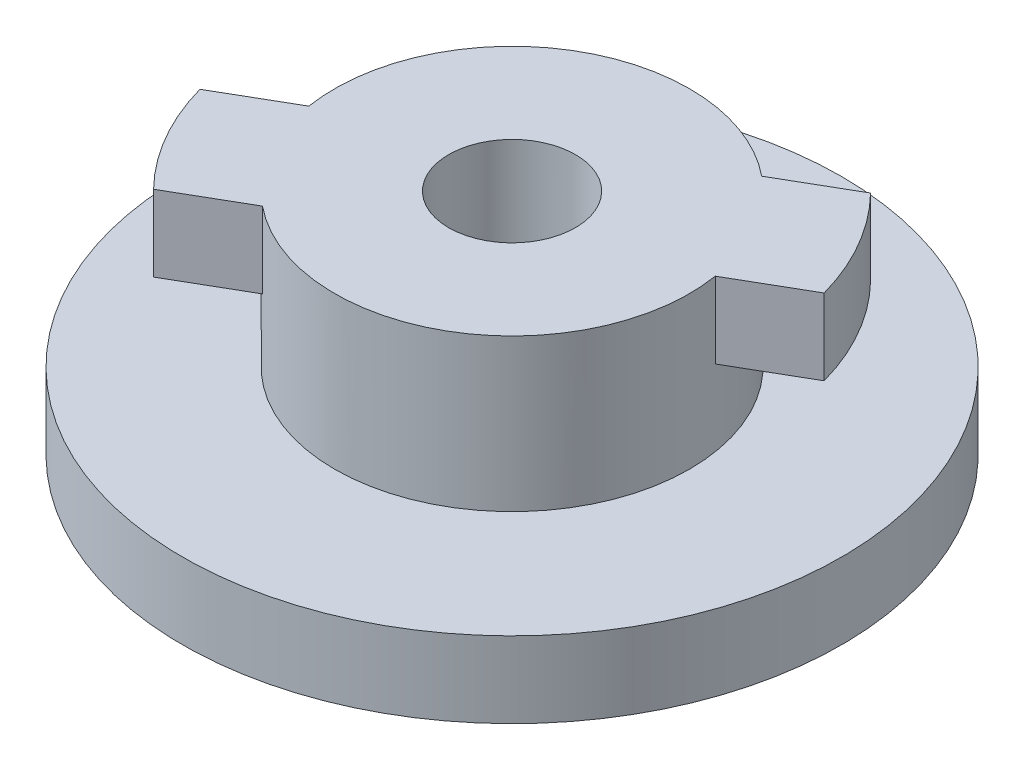
SolidWorks part; units mm, degrees
ref_plane "Front Plane" through (0, 0, 0) normal (0, 0, 1) x (1, 0, 0)
ref_plane "Top Plane" through (0, 0, 0) normal (0, 1, 0) x (1, 0, 0)
ref_plane "Right Plane" through (0, 0, 0) normal (1, 0, 0) x (0, 0, -1)
sketch "Sketch1" plane through (0, 0, 0) normal (0, 1, 0) x (-1, 0, 0)
  line L0 (0, -63.094) -> (22.5167, -50.094) construction
  line L1 (4.4124, -57.6598) -> (7.1353, -56.0877)
  line L2 (6.9124, -61.9899) -> (9.6353, -60.4178)
  line L9 (-4.4124, -68.5282) -> (-7.1353, -70.1003)
  line L10 (-6.9124, -64.1981) -> (-9.6353, -65.7702)
  arc A29 (-9.6353, -65.7702) -> (-7.1353, -70.1003) centre (0, -63.094) ccw
  arc A30 (-6.9124, -64.1981) -> (-4.4124, -68.5282) centre (0, -63.094) ccw construction
  arc A31 (7.1353, -56.0877) -> (-9.6353, -65.7702) centre (0, -63.094) ccw construction
  arc A32 (4.4124, -57.6598) -> (-6.9124, -64.1981) centre (0, -63.094) ccw
  arc A33 (6.9124, -61.9899) -> (4.4124, -57.6598) centre (0, -63.094) ccw construction
  arc A34 (-4.4124, -68.5282) -> (6.9124, -61.9899) centre (0, -63.094) ccw
  arc A35 (9.6353, -60.4178) -> (7.1353, -56.0877) centre (0, -63.094) ccw
  arc A36 (-7.1353, -70.1003) -> (9.6353, -60.4178) centre (0, -63.094) ccw construction
  dimension "D3" = 2
  dimension "D2" = 2.5
extrude "Boss-Extrude1" add sketch "Sketch1" along normal blind 3
sketch "Sketch2" plane through (0, 0, 0) normal (0, -1, 0) x (1, 0, 0)
  circle A0 centre (0, -63.094) radius 7
  arc A1 (-6.9124, -61.9899) -> (4.4124, -68.5282) centre (0, -63.094) ccw construction
extrude "Boss-Extrude2" add sketch "Sketch2" along normal blind 3
sketch "Sketch3" plane through (0, -3, 0) normal (0, -1, 0) x (1, 0, 0)
  circle A0 centre (0, -63.094) radius 7 construction
  circle A2 centre (0, -63.094) radius 7 construction
  circle A3 centre (0, -63.094) radius 13
  dimension "D1" = 26
extrude "Boss-Extrude3" add sketch "Sketch3" along normal blind 3
sketch "Sketch4" plane through (0, 3, 0) normal (0, 1, 0) x (1, 0, 0)
  circle A0 centre (0, 63.094) radius 7 construction
  circle A1 centre (0, 63.094) radius 7 construction
  circle A2 centre (0, 63.094) radius 2.5
  dimension "D1" = 5
extrude "Cut-Extrude1" cut sketch "Sketch4" against normal blind 20
